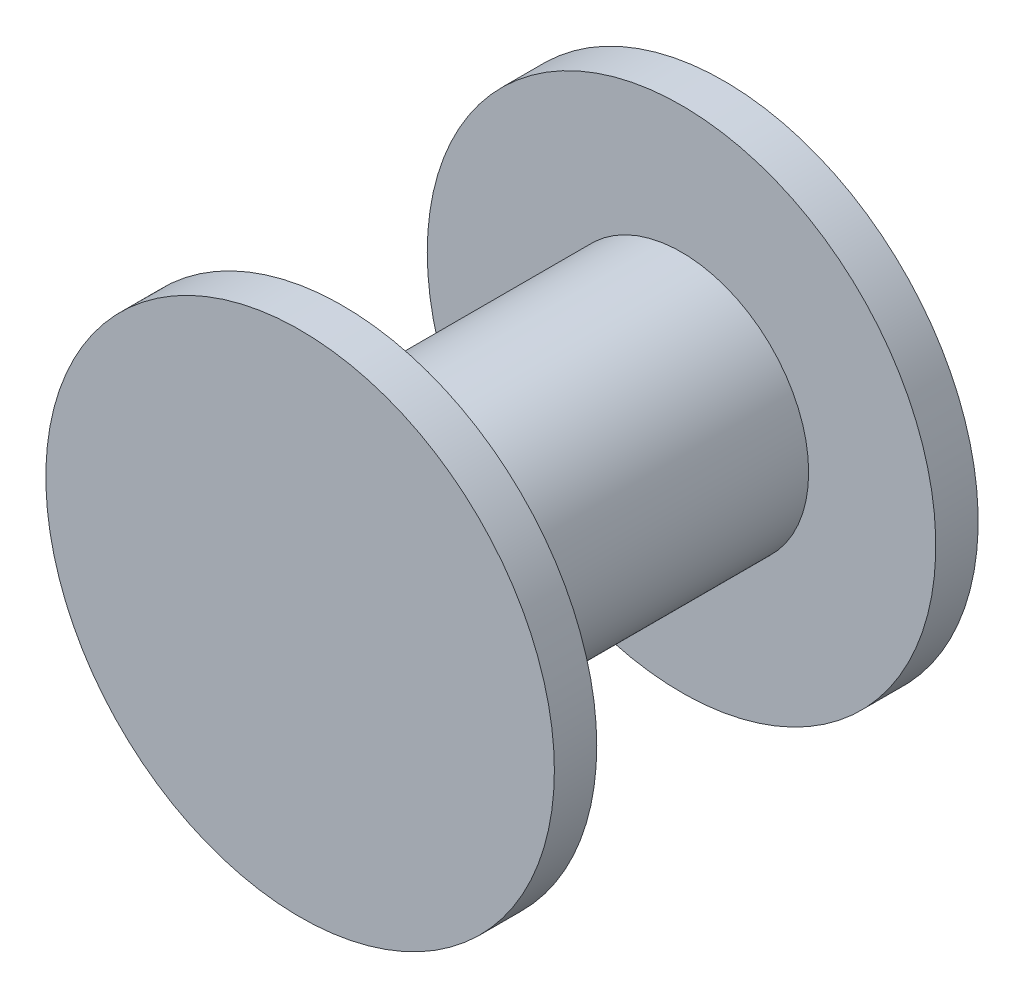
SolidWorks part; units mm, degrees
ref_plane "Front Plane" through (0, 0, 0) normal (0, 0, 1) x (1, 0, 0)
ref_plane "Top Plane" through (0, 0, 0) normal (0, 1, 0) x (1, 0, 0)
ref_plane "Right Plane" through (0, 0, 0) normal (1, 0, 0) x (0, 0, -1)
sketch "Sketch1" plane through (0, 0, 0) normal (0, 0, 1) x (1, 0, 0)
  circle A0 centre (0, 0) radius 9.525
  dimension "D1" = 19.05
extrude "Boss-Extrude1" add sketch "Sketch1" along normal blind 25.4
sketch "Sketch2" plane through (0, 0, 25.4) normal (0, 0, 1) x (1, 0, 0)
  circle A0 centre (0, -0.2904) radius 19.05
  dimension "D1" = 38.1
extrude "Boss-Extrude2" add sketch "Sketch2" along normal blind 3.175
sketch "Sketch3" plane through (0, 0, 0) normal (0, 0, -1) x (-1, 0, 0)
  circle A0 centre (0, 0) radius 19.05
  dimension "D1" = 38.1
extrude "Boss-Extrude3" add sketch "Sketch3" along normal blind 3.175
